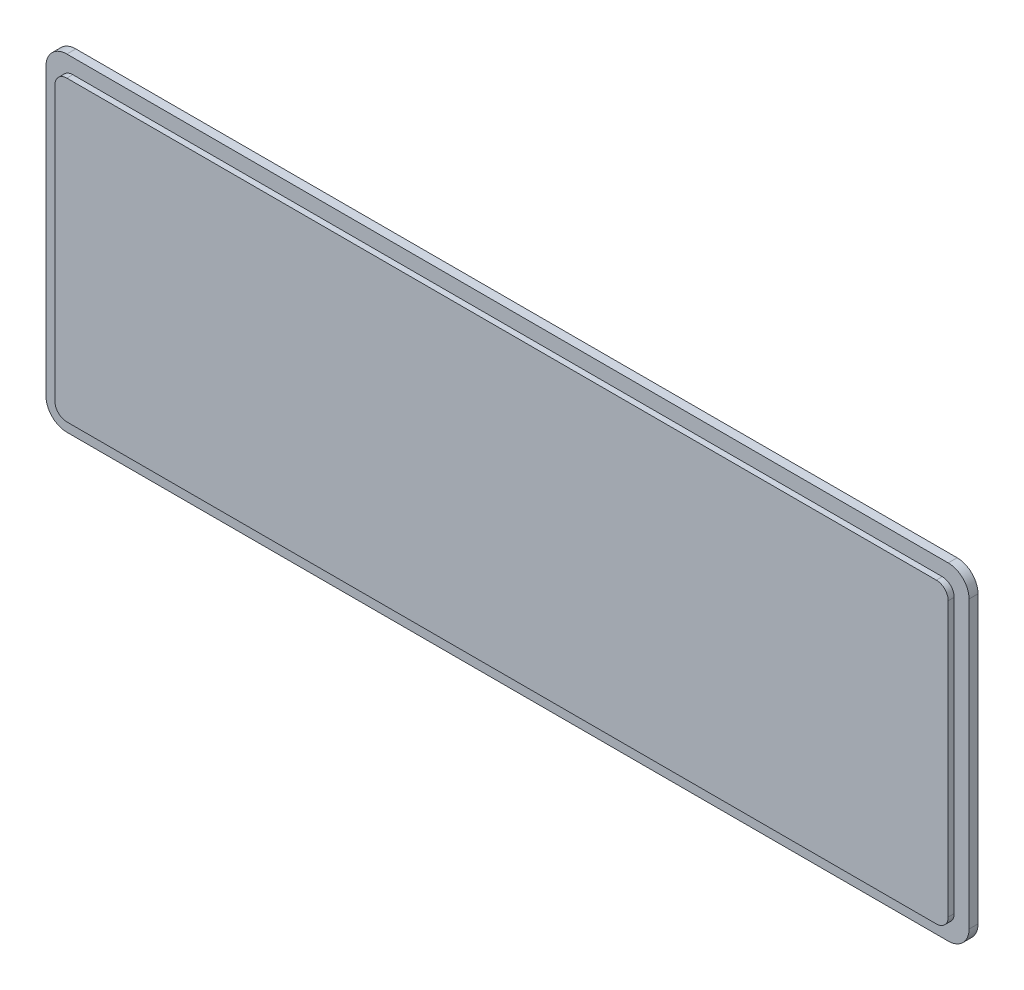
SolidWorks part; units mm, degrees
ref_plane "前视基准面" through (0, 0, 0) normal (0, 0, 1) x (1, 0, 0)
ref_plane "上视基准面" through (0, 0, 0) normal (0, 1, 0) x (1, 0, 0)
ref_plane "右视基准面" through (0, 0, 0) normal (1, 0, 0) x (0, 0, -1)
other "Configuration Table"
sketch "草图1" plane through (0, 0, 0) normal (0, 0, 1) x (1, 0, 0)
  line L1 (0, 0) -> (155, 0)
  line L2 (0, 0) -> (0, -55)
  line L3 (0, -55) -> (155, -55)
  line L4 (155, 0) -> (155, -55)
  dimension "D1" = 155
  dimension "D2" = 55
extrude "凸台-拉伸1" add sketch "草图1" along normal blind 1.5
fillet "圆角1" radius 3.5 4 edges at (0, -55, 0.75) (155, -55, 0.75) (155, 0, 0.75) (0, 0, 0.75)
sketch "草图2" plane through (0, 0, 1.5) normal (0, 0, 1) x (1, 0, 0)
  line L0 (155, -51.5) -> (155, -3.5) construction
  line L1 (2.5, -2.5) -> (152.5, -2.5)
  line L2 (2.5, -2.5) -> (2.5, -52.5)
  line L3 (2.5, -52.5) -> (152.5, -52.5)
  line L4 (152.5, -2.5) -> (152.5, -52.5)
  line L5 (3.5, -55) -> (151.5, -55) construction
  dimension "D1" = 50
  dimension "D2" = 150
  dimension "D3" = 2.5
  dimension "D4" = 2.5
extrude "凸台-拉伸2" add sketch "草图2" along normal blind 1
fillet "圆角3" radius 2 4 edges at (2.5, -52.5, 2) (152.5, -52.5, 2) (152.5, -2.5, 2) (2.5, -2.5, 2)
